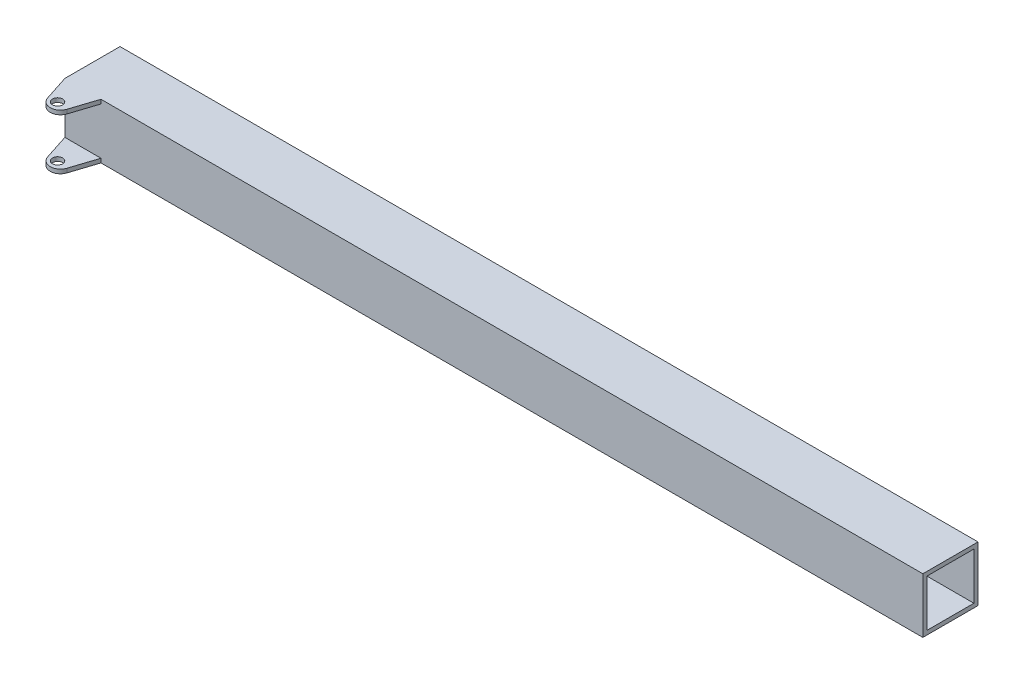
SolidWorks part; units mm, degrees
material "Plain Carbon Steel"
ref_plane "Front Plane" through (0, 0, 0) normal (0, 0, 1) x (1, 0, 0)
ref_plane "Top Plane" through (0, 0, 0) normal (0, 1, 0) x (1, 0, 0)
ref_plane "Right Plane" through (0, 0, 0) normal (1, 0, 0) x (0, 0, -1)
sketch "Sketch1" plane through (0, 0, 0) normal (1, 0, 0) x (0, 0, -1)
  line L1 (135, 270) -> (135, 0)
  line L3 (135, 0) -> (-135, 0)
  line L5 (-135, 270) -> (135, 270)
  line L6 (-135, 270) -> (-135, 0)
  line L7 (-135, 20) -> (-115, 20) construction
  line L8 (-115, 250) -> (115, 250)
  line L9 (-115, 250) -> (-115, 20)
  line L10 (-115, 20) -> (115, 20)
  line L11 (115, 250) -> (115, 20)
  line L12 (115, 250) -> (115, 270) construction
  line L13 (115, 250) -> (135, 250) construction
  line L14 (-115, 20) -> (-115, 0) construction
  dimension "D1" = 270
  dimension "D2" = 20
  dimension "D4" = 270
extrude "Boss-Extrude1" add sketch "Sketch1" against normal blind 4200
sketch "Sketch2" plane through (0, 0, 0) normal (0, -1, 0) x (1, 0, 0)
  line L0 (0, 135) -> (0, -135) construction
  circle A0 centre (-200, 0) radius 25
  dimension "D1" = 50
  dimension "D2" = 200
extrude "Boss-Extrude2" add sketch "Sketch2" against normal through all
sketch "Sketch3" plane through (0, 0, 0) normal (0, 1, 0) x (1, 0, 0)
  line L0 (-4023.2453, -135) -> (-4064.0768, -260.4725)
  line L1 (-4200, -135) -> (0, -135) construction
  line L2 (-4159.1684, -260.4725) -> (-4200, -135)
  line L3 (-4200, -135) -> (-4023.2453, -135)
  arc A1 (-4159.1684, -260.4725) -> (-4064.0768, -260.4725) centre (-4111.6226, -245) ccw
  circle A2 centre (-4118.2165, -252.56) radius 25
  point P13 (-4111.6226, -135)
  dimension "D1" = 50
  dimension "D3" = 50
  dimension "D2" = 110
  dimension "D4" = 117.56
extrude "Boss-Extrude3" add sketch "Sketch3" along normal blind 20
ref_plane "Plane1" through (0, 135, 0) normal (0, -1, 0) x (-1, 0, 0)
mirror "Mirror1" about plane through (0, 135, 0) normal (0, -1, 0) of "Boss-Extrude3"
